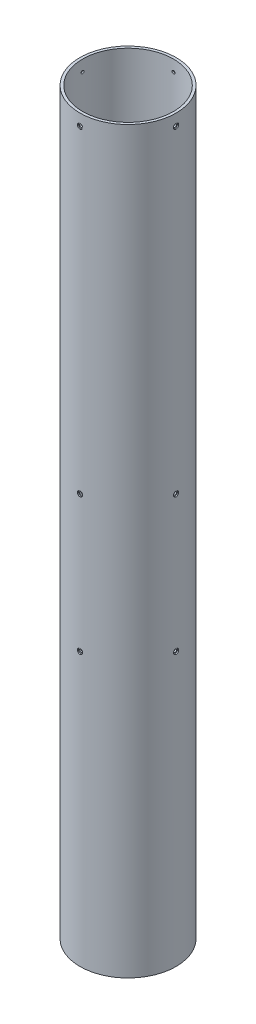
SolidWorks part; units mm, degrees
material "Hexcel AS4C (3000 Filaments)"
ref_plane "Front Plane" through (0, 0, 0) normal (0, 0, 1) x (1, 0, 0)
ref_plane "Top Plane" through (0, 0, 0) normal (0, 1, 0) x (1, 0, 0)
ref_plane "Right Plane" through (0, 0, 0) normal (1, 0, 0) x (0, 0, -1)
sketch "Sketch1" plane through (0, 0, 0) normal (0, 1, 0) x (1, 0, 0)
  circle A0 centre (0, 0) radius 50.8
  dimension "D1" = 101.6
extrude "Tube Extrusion" add sketch "Sketch1" along normal blind 825.5 thin
ref_plane "Hole Plane" through (0, 0, 53.721) normal (0, 0, 1) x (1, 0, 0)
sketch "Sketch3" plane through (0, 0, 53.721) normal (0, 0, 1) x (1, 0, 0)
  line L0 (0, 825.5) -> (0, 0) construction
  line L1 (50.8, 825.5) -> (-50.8, 825.5) construction
  line L2 (53.721, 825.5) -> (-53.721, 825.5) construction
  circle A0 centre (0, 457.2) radius 1.6383
  circle A1 centre (0, 304.8) radius 1.6383
  circle A2 centre (0, 812.8) radius 1.6383
  dimension "D1" = 3.2766
  dimension "D3" = 3.2766
  dimension "D5" = 3.2766
  dimension "D2" = 368.3
  dimension "D4" = 520.7
  dimension "D6" = 12.7
extrude "Bulkhead Holes" cut sketch "Sketch3" against normal up to next
pattern_circular "Hole Pattern" count 4 over 360 about axis through (0, 825.5, 0) along (0, -1, 0) of "Bulkhead Holes"
sketch "Sketch4" plane through (0, 0, 53.721) normal (0, 0, 1) x (1, 0, 0)
  circle A0 centre (0, 304.8) radius 1.6383 construction
  circle A1 centre (0, 457.2) radius 1.6383 construction
  circle A2 centre (0, 812.8) radius 1.6383 construction
  circle A3 centre (0, 304.8) radius 1.6383
  circle A4 centre (0, 457.2) radius 1.6383
  circle A5 centre (0, 812.8) radius 1.6383
  circle A6 centre (0, 812.8) radius 2.9083
  circle A7 centre (0, 457.2) radius 2.9083
  circle A8 centre (0, 304.8) radius 2.9083
  dimension "D1" = 1.27
  dimension "D2" = 1.27
extrude "Cut-Extrude1" cut sketch "Sketch4" against normal blind 1.27
pattern_circular "CirPattern1" count 4 over 360 about axis through (0, 0, 0) along (0, 1, 0) of "Cut-Extrude1"
